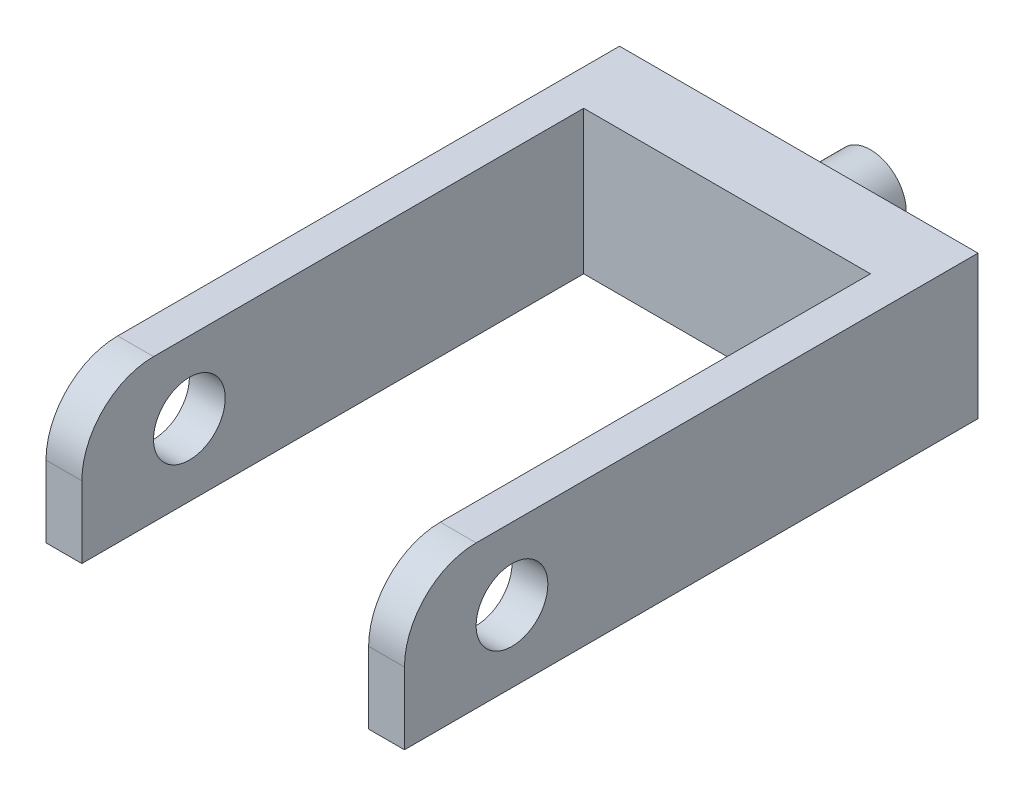
SolidWorks part; units mm, degrees
ref_plane "Front Plane" through (0, 0, 0) normal (0, 0, 1) x (1, 0, 0)
ref_plane "Top Plane" through (0, 0, 0) normal (0, 1, 0) x (1, 0, 0)
ref_plane "Right Plane" through (0, 0, 0) normal (1, 0, 0) x (0, 0, -1)
sketch "Sketch1" plane through (0, 0, 0) normal (0, 1, 0) x (1, 0, 0)
  line L5 (0, 0) -> (-127, 0)
  line L6 (0, 0) -> (0, -203.2)
  line L7 (0, -203.2) -> (-127, -203.2)
  line L8 (-127, 0) -> (-127, -203.2)
extrude "Boss-Extrude1" add sketch "Sketch1" along normal blind 50.8
sketch "Sketch3" plane through (0, 50.8, 0) normal (0, 1, 0) x (1, 0, 0)
  line L0 (-63.5, -203.2) -> (-63.5, -25.4) construction
  line L3 (-127, -203.2) -> (0, -203.2) construction
  line L4 (-63.5, -25.4) -> (-12.7, -25.4)
  line L5 (-63.5, -25.4) -> (-114.3, -25.4)
  line L6 (-114.3, -25.4) -> (-114.3, -203.2)
  line L7 (-12.7, -25.4) -> (-12.7, -203.2)
  line L8 (-12.7, -203.2) -> (-114.3, -203.2)
extrude "Cut-Extrude1" cut sketch "Sketch3" against normal blind 254
sketch "Sketch4" plane through (0, 0, 0) normal (1, 0, 0) x (0, 0, -1)
  line L0 (-203.2, 25.4) -> (-165.1, 25.4) construction
  line L1 (-203.2, 50.8) -> (-203.2, 0) construction
  circle A0 centre (-165.1, 25.4) radius 12.7
extrude "Cut-Extrude2" cut sketch "Sketch4" against normal blind 254
sketch "Sketch5" plane through (0, 0, 0) normal (0, 0, -1) x (-1, 0, 0)
  line L0 (0, 50.8) -> (127, 0) construction
  circle A0 centre (63.5, 25.4) radius 12.7
extrude "Boss-Extrude2" add sketch "Sketch5" along normal blind 25.4
sketch "Sketch6" plane through (0, 0, -25.4) normal (0, 0, -1) x (-1, 0, 0)
  circle A0 centre (63.5, 25.4) radius 12.7 construction
fillet "Fillet1" radius 25.4 1 edges at (-120.65, 50.8, 203.2)
fillet "Fillet2" radius 25.4 1 edges at (-6.35, 50.8, 203.2)
